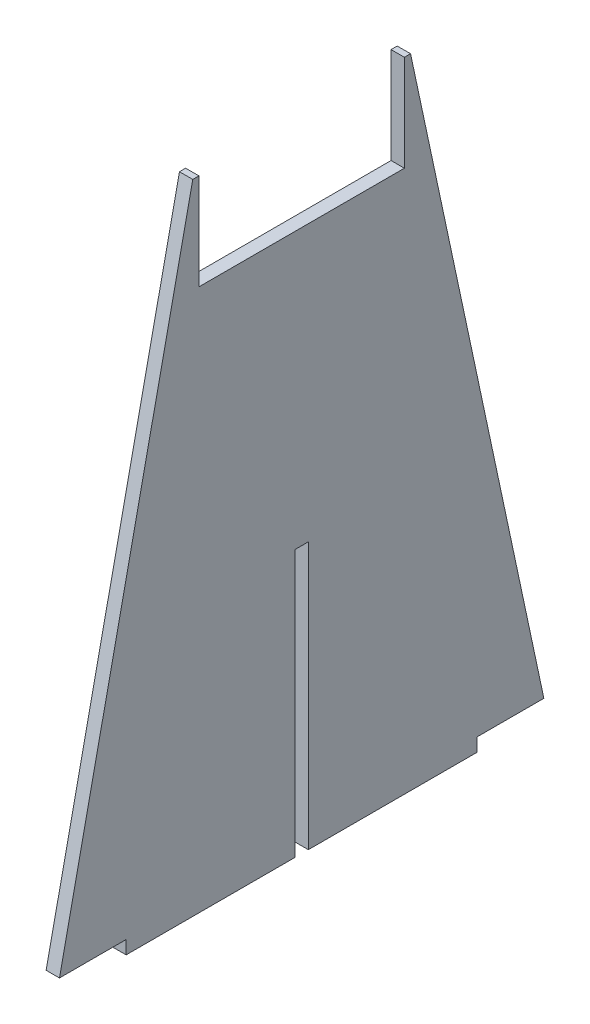
SolidWorks part; units mm, degrees
ref_plane "Спереди" through (0, 0, 0) normal (0, 0, 1) x (1, 0, 0)
ref_plane "Сверху" through (0, 0, 0) normal (0, 1, 0) x (1, 0, 0)
ref_plane "Справа" through (0, 0, 0) normal (1, 0, 0) x (0, 0, -1)
sketch "Эскиз1" plane through (0, 0, 0) normal (1, 0, 0) x (0, 0, -1)
  line L0 (0, 0) -> (0, 119) construction
  line L6 (54.5, 0) -> (29.1133, 119)
  line L7 (54.5, 0) -> (39.5, 0)
  line L8 (39.5, 0) -> (39.5, -3)
  line L9 (39.5, -3) -> (1.5, -3)
  line L10 (-39.5, -3) -> (-1.5, -3)
  line L11 (-39.5, 0) -> (-39.5, -3)
  line L12 (-54.5, 0) -> (-39.5, 0)
  line L13 (-54.5, 0) -> (-29.1133, 119)
  line L14 (-1.5, 57) -> (-1.5, -3)
  line L15 (1.5, -3) -> (1.5, 57)
  line L16 (29.1133, 119) -> (-29.1133, 119)
  line L17 (1.5, 57) -> (-1.5, 57)
  point P16 (0, 75)
extrude "Бобышка-Вытянуть1" add sketch "Эскиз1" along normal blind 3
sketch "Sketch1" plane through (3, 0, 0) normal (1, 0, 0) x (0, 0, -1)
  line L0 (-29.1133, 119) -> (-24.5, 140.625)
  line L1 (-24.5, 140.625) -> (-23.1133, 140.625)
  line L2 (-23.1133, 140.625) -> (-23.1133, 119)
  line L3 (29.1133, 119) -> (-29.1133, 119) construction
  line L4 (-23.1133, 119) -> (-29.1133, 119)
  line L5 (29.1133, 119) -> (24.5, 140.625)
  line L6 (24.5, 140.625) -> (23.1133, 140.625)
  line L7 (23.1133, 140.625) -> (23.1133, 119)
  line L8 (23.1133, 119) -> (29.1133, 119)
  line L9 (-29.1133, 119) -> (-54.5, 0) construction
  line L10 (54.5, 0) -> (29.1133, 119) construction
  point P10 (-23.1133, 136.3061)
  point P13 (0, 0)
  dimension "D1" = 6
  dimension "D2" = 6
  dimension "D3" = 49
extrude "Boss-Extrude1" add sketch "Sketch1" against normal up to surface (3 mm away) up to face at (0, 28.3333, 0)
